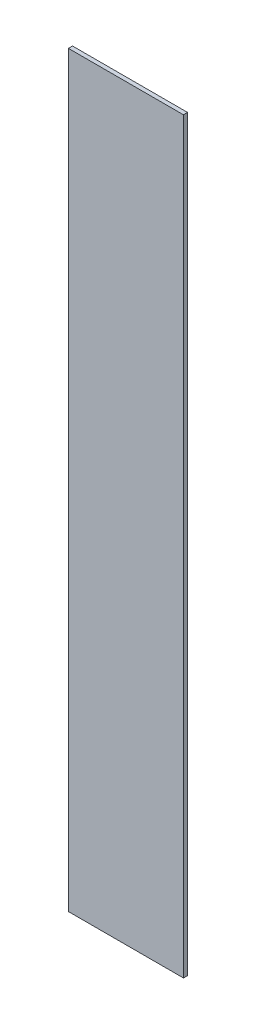
SolidWorks part; units mm, degrees
ref_plane "Front Plane" through (0, 0, 0) normal (0, 0, 1) x (1, 0, 0)
ref_plane "Top Plane" through (0, 0, 0) normal (0, 1, 0) x (1, 0, 0)
ref_plane "Right Plane" through (0, 0, 0) normal (1, 0, 0) x (0, 0, -1)
other "Configuration Table"
sketch "Sketch1" plane through (0, 0, 0) normal (0, 0, 1) x (1, 0, 0)
  line L1 (623, 1724) -> (651, 1724)
  line L2 (623, 1724) -> (623, 1906)
  line L3 (623, 1906) -> (651, 1906)
  line L4 (651, 1724) -> (651, 1906)
extrude "OVEN_fan_filtre_kapagi_kulp_cukuru_1" add sketch "Sketch1" along normal blind 1 from offset 26 separate body
